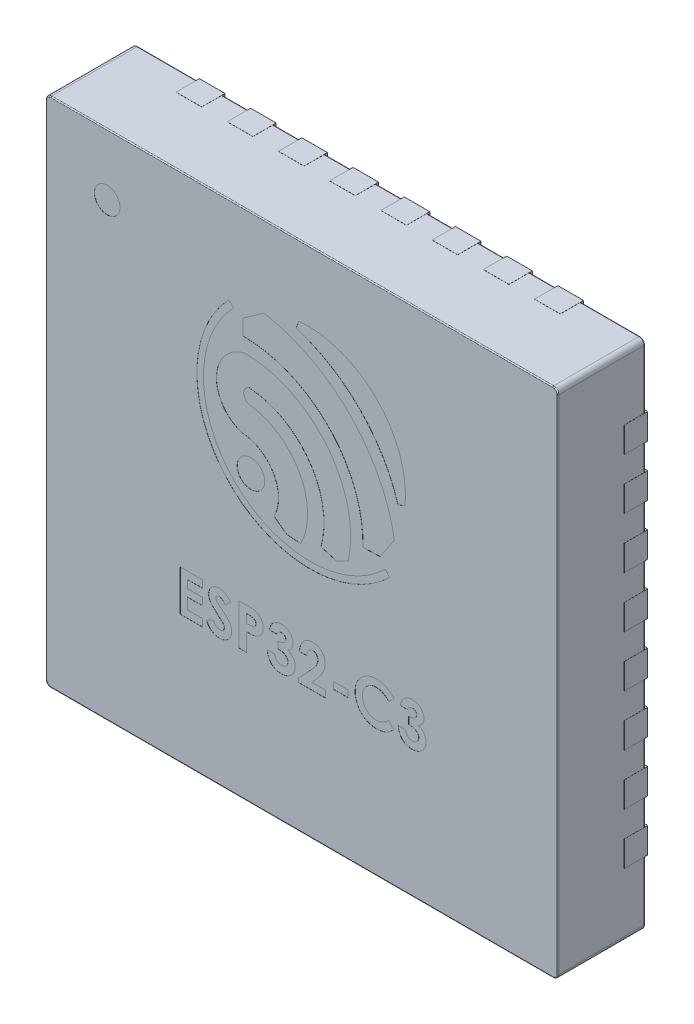
SolidWorks part; units mm, degrees
other "ESP32-C3-SoC" parameters "D5"=0.3678, "D12"=0.3401, "D13"=0.0424, "D1"=3.1308, "D2"=3.0402, "D3"=0.4115, "D4"=0.3, "D6"=0.3296, "D7"=0.2637, "D8"=0.9806, "D10"=0.5, "D11"=0.25, "D9"=4
ref_plane "Front Plane" through (0, 0, 0) normal (0, 0, 1) x (1, 0, 0)
ref_plane "Top Plane" through (0, 0, 0) normal (0, 1, 0) x (1, 0, 0)
ref_plane "Right Plane" through (0, 0, 0) normal (1, 0, 0) x (0, 0, -1)
sketch "Sketch1" plane through (0, 0, 0) normal (0, 1, 0) x (1, 0, 0)
  line L1 (-2.5, -2.5) -> (2.5, -2.5)
  line L2 (-2.5, -2.5) -> (-2.5, 2.5)
  line L3 (-2.5, 2.5) -> (2.5, 2.5)
  line L4 (2.5, -2.5) -> (2.5, 2.5)
  line L5 (-2.5, -2.5) -> (2.5, 2.5) construction
  line L6 (-2.5, 2.5) -> (2.5, -2.5) construction
  point P0 (0, 0)
  dimension "D1" = 5
  dimension "D2" = 5
extrude "Boss-Extrude1" add sketch "Sketch1" along normal blind 0.85
fillet "Fillet1" radius 0.05 4 edges at (2.5, 0.425, -2.5) (2.5, 0.425, 2.5) (-2.5, 0.425, 2.5) (-2.5, 0.425, -2.5)
fillet "Fillet2" radius 0.01 16 edges at (2.4854, 0.85, 2.4854) (0, 0.85, 2.5) (-2.4854, 0.85, 2.4854) (-2.5, 0.85, 0) (-2.4854, 0.85, -2.4854) (0, 0.85, -2.5) (2.4854, 0.85, -2.4854) (2.5, 0.85, 0) (2.5, 0, 0) (2.4854, 0, -2.4854) (0, 0, -2.5) (2.4854, 0, 2.4854) (0, 0, 2.5) (-2.4854, 0, 2.4854) (-2.5, 0, 0) (-2.4854, 0, -2.4854)
sketch "Sketch2" plane through (0, 0, 0) normal (0, -1, 0) x (1, 0, 0)
  line L0 (1.5573, 1.8427) -> (1.8427, 1.5573)
  line L1 (-1.825, -1.85) -> (1.825, -1.85)
  line L2 (-1.85, -1.825) -> (-1.85, 1.825)
  line L3 (-1.825, 1.85) -> (1.5396, 1.85)
  line L4 (1.85, -1.825) -> (1.85, 1.5396)
  line L5 (-1.8427, -1.8427) -> (1.85, 1.85) construction
  line L6 (-1.8427, 1.8427) -> (1.8427, -1.8427) construction
  line L7 (1.55, 1.85) -> (1.85, 1.85) construction
  line L8 (1.85, 1.55) -> (1.85, 1.85) construction
  line L9 (-1.85, 1.85) -> (-1.825, 1.85) construction
  line L10 (-1.85, 1.85) -> (-1.8427, 1.8427) construction
  line L11 (-1.85, 1.825) -> (-1.85, 1.85) construction
  line L12 (-1.85, -1.85) -> (-1.85, -1.825) construction
  line L13 (-1.85, -1.85) -> (-1.8427, -1.8427) construction
  line L14 (-1.85, -1.85) -> (-1.825, -1.85) construction
  line L15 (1.85, -1.85) -> (1.85, -1.825) construction
  line L16 (1.8427, -1.8427) -> (1.85, -1.85) construction
  line L17 (1.825, -1.85) -> (1.85, -1.85) construction
  line L18 (0, -1000) -> (0, 49000) construction
  line L23 (-0.375, 2.501) -> (-0.125, 2.501)
  line L24 (-0.375, 2.501) -> (-0.375, 2.101)
  line L25 (-0.375, 2.101) -> (-0.125, 2.101)
  line L26 (-0.125, 2.501) -> (-0.125, 2.101)
  line L27 (-0.375, 2.501) -> (-0.125, 2.101) construction
  line L28 (-0.375, 2.101) -> (-0.125, 2.501) construction
  line L30 (-0.875, 2.501) -> (-0.875, 2.101)
  line L31 (-0.875, 2.501) -> (-0.625, 2.501)
  line L32 (-0.625, 2.501) -> (-0.625, 2.101)
  line L33 (-0.875, 2.101) -> (-0.625, 2.101)
  line L34 (-0.875, 2.101) -> (-0.625, 2.501) construction
  line L35 (-0.875, 2.501) -> (-0.625, 2.101) construction
  line L36 (-1.375, 2.501) -> (-1.375, 2.101)
  line L37 (-1.375, 2.501) -> (-1.125, 2.501)
  line L38 (-1.125, 2.501) -> (-1.125, 2.101)
  line L39 (-1.375, 2.101) -> (-1.125, 2.101)
  line L40 (-1.375, 2.101) -> (-1.125, 2.501) construction
  line L41 (-1.375, 2.501) -> (-1.125, 2.101) construction
  line L42 (-1.875, 2.501) -> (-1.875, 2.101)
  line L43 (-1.875, 2.501) -> (-1.625, 2.501)
  line L44 (-1.625, 2.501) -> (-1.625, 2.101)
  line L45 (-1.875, 2.101) -> (-1.625, 2.101)
  line L46 (-1.875, 2.101) -> (-1.625, 2.501) construction
  line L47 (-1.875, 2.501) -> (-1.625, 2.101) construction
  line L48 (-0.375, 2.501) -> (-0.875, 2.501) construction
  line L49 (1.5396, 1.85) -> (1.55, 1.85) construction
  line L66 (1.55, 1.85) -> (1.5573, 1.8427) construction
  line L162 (-1000, 0) -> (49000, 0) construction
  line L163 (-2.5, 2.5) -> (2.5, 2.5) construction
  line L164 (0.375, 2.501) -> (0.875, 2.501) construction
  line L165 (1.875, 2.501) -> (1.625, 2.101) construction
  line L166 (1.875, 2.101) -> (1.625, 2.501) construction
  line L167 (1.375, 2.501) -> (1.125, 2.101) construction
  line L168 (1.375, 2.101) -> (1.125, 2.501) construction
  line L169 (0.875, 2.501) -> (0.625, 2.101) construction
  line L170 (0.875, 2.101) -> (0.625, 2.501) construction
  line L171 (0.375, 2.101) -> (0.125, 2.501) construction
  line L172 (0.375, 2.501) -> (0.125, 2.101) construction
  line L173 (1.875, 2.101) -> (1.625, 2.101)
  line L174 (1.625, 2.501) -> (1.625, 2.101)
  line L175 (1.875, 2.501) -> (1.625, 2.501)
  line L176 (1.875, 2.501) -> (1.875, 2.101)
  line L177 (1.375, 2.101) -> (1.125, 2.101)
  line L178 (1.125, 2.501) -> (1.125, 2.101)
  line L179 (1.375, 2.501) -> (1.125, 2.501)
  line L180 (1.375, 2.501) -> (1.375, 2.101)
  line L181 (0.875, 2.101) -> (0.625, 2.101)
  line L182 (0.625, 2.501) -> (0.625, 2.101)
  line L183 (0.875, 2.501) -> (0.625, 2.501)
  line L184 (0.875, 2.501) -> (0.875, 2.101)
  line L185 (0.125, 2.501) -> (0.125, 2.101)
  line L186 (0.375, 2.101) -> (0.125, 2.101)
  line L187 (0.375, 2.501) -> (0.375, 2.101)
  line L188 (0.375, 2.501) -> (0.125, 2.501)
  line L189 (0.375, -2.501) -> (0.125, -2.101) construction
  line L190 (0.375, -2.101) -> (0.125, -2.501) construction
  line L191 (0.875, -2.101) -> (0.625, -2.501) construction
  line L192 (0.875, -2.501) -> (0.625, -2.101) construction
  line L193 (1.375, -2.101) -> (1.125, -2.501) construction
  line L194 (1.375, -2.501) -> (1.125, -2.101) construction
  line L195 (1.875, -2.101) -> (1.625, -2.501) construction
  line L196 (1.875, -2.501) -> (1.625, -2.101) construction
  line L197 (0.375, -2.501) -> (0.875, -2.501) construction
  line L198 (-0.375, -2.501) -> (-0.875, -2.501) construction
  line L199 (-1.875, -2.501) -> (-1.625, -2.101) construction
  line L200 (-1.875, -2.101) -> (-1.625, -2.501) construction
  line L201 (-1.375, -2.501) -> (-1.125, -2.101) construction
  line L202 (-1.375, -2.101) -> (-1.125, -2.501) construction
  line L203 (-0.875, -2.501) -> (-0.625, -2.101) construction
  line L204 (-0.875, -2.101) -> (-0.625, -2.501) construction
  line L205 (-0.375, -2.101) -> (-0.125, -2.501) construction
  line L206 (-0.375, -2.501) -> (-0.125, -2.101) construction
  line L207 (0.375, -2.501) -> (0.125, -2.501)
  line L208 (0.375, -2.501) -> (0.375, -2.101)
  line L209 (0.375, -2.101) -> (0.125, -2.101)
  line L210 (0.125, -2.501) -> (0.125, -2.101)
  line L211 (0.875, -2.501) -> (0.875, -2.101)
  line L212 (0.875, -2.501) -> (0.625, -2.501)
  line L213 (0.625, -2.501) -> (0.625, -2.101)
  line L214 (0.875, -2.101) -> (0.625, -2.101)
  line L215 (1.375, -2.501) -> (1.375, -2.101)
  line L216 (1.375, -2.501) -> (1.125, -2.501)
  line L217 (1.125, -2.501) -> (1.125, -2.101)
  line L218 (1.375, -2.101) -> (1.125, -2.101)
  line L219 (1.875, -2.501) -> (1.875, -2.101)
  line L220 (1.875, -2.501) -> (1.625, -2.501)
  line L221 (1.625, -2.501) -> (1.625, -2.101)
  line L222 (1.875, -2.101) -> (1.625, -2.101)
  line L223 (-1.875, -2.101) -> (-1.625, -2.101)
  line L224 (-1.625, -2.501) -> (-1.625, -2.101)
  line L225 (-1.875, -2.501) -> (-1.625, -2.501)
  line L226 (-1.875, -2.501) -> (-1.875, -2.101)
  line L227 (-1.375, -2.101) -> (-1.125, -2.101)
  line L228 (-1.125, -2.501) -> (-1.125, -2.101)
  line L229 (-1.375, -2.501) -> (-1.125, -2.501)
  line L230 (-1.375, -2.501) -> (-1.375, -2.101)
  line L231 (-0.875, -2.101) -> (-0.625, -2.101)
  line L232 (-0.625, -2.501) -> (-0.625, -2.101)
  line L233 (-0.875, -2.501) -> (-0.625, -2.501)
  line L234 (-0.875, -2.501) -> (-0.875, -2.101)
  line L235 (-0.125, -2.501) -> (-0.125, -2.101)
  line L236 (-0.375, -2.101) -> (-0.125, -2.101)
  line L237 (-0.375, -2.501) -> (-0.375, -2.101)
  line L238 (-0.375, -2.501) -> (-0.125, -2.501)
  line L239 (2.501, 0.375) -> (2.101, 0.125) construction
  line L240 (2.101, 0.375) -> (2.501, 0.125) construction
  line L241 (2.101, 0.875) -> (2.501, 0.625) construction
  line L242 (2.501, 0.875) -> (2.101, 0.625) construction
  line L243 (2.101, 1.375) -> (2.501, 1.125) construction
  line L244 (2.501, 1.375) -> (2.101, 1.125) construction
  line L245 (2.101, 1.875) -> (2.501, 1.625) construction
  line L246 (2.501, 1.875) -> (2.101, 1.625) construction
  line L247 (2.501, 0.375) -> (2.501, 0.875) construction
  line L248 (2.501, -0.375) -> (2.501, -0.875) construction
  line L249 (2.501, -1.875) -> (2.101, -1.625) construction
  line L250 (2.101, -1.875) -> (2.501, -1.625) construction
  line L251 (2.501, -1.375) -> (2.101, -1.125) construction
  line L252 (2.101, -1.375) -> (2.501, -1.125) construction
  line L253 (2.501, -0.875) -> (2.101, -0.625) construction
  line L254 (2.101, -0.875) -> (2.501, -0.625) construction
  line L255 (2.101, -0.375) -> (2.501, -0.125) construction
  line L256 (2.501, -0.375) -> (2.101, -0.125) construction
  line L257 (2.501, 0.375) -> (2.501, 0.125)
  line L258 (2.501, 0.375) -> (2.101, 0.375)
  line L259 (2.101, 0.375) -> (2.101, 0.125)
  line L260 (2.501, 0.125) -> (2.101, 0.125)
  line L261 (2.501, 0.875) -> (2.101, 0.875)
  line L262 (2.501, 0.875) -> (2.501, 0.625)
  line L263 (2.501, 0.625) -> (2.101, 0.625)
  line L264 (2.101, 0.875) -> (2.101, 0.625)
  line L265 (2.501, 1.375) -> (2.101, 1.375)
  line L266 (2.501, 1.375) -> (2.501, 1.125)
  line L267 (2.501, 1.125) -> (2.101, 1.125)
  line L268 (2.101, 1.375) -> (2.101, 1.125)
  line L269 (2.501, 1.875) -> (2.101, 1.875)
  line L270 (2.501, 1.875) -> (2.501, 1.625)
  line L271 (2.501, 1.625) -> (2.101, 1.625)
  line L272 (2.101, 1.875) -> (2.101, 1.625)
  line L273 (2.101, -1.875) -> (2.101, -1.625)
  line L274 (2.501, -1.625) -> (2.101, -1.625)
  line L275 (2.501, -1.875) -> (2.501, -1.625)
  line L276 (2.501, -1.875) -> (2.101, -1.875)
  line L277 (2.101, -1.375) -> (2.101, -1.125)
  line L278 (2.501, -1.125) -> (2.101, -1.125)
  line L279 (2.501, -1.375) -> (2.501, -1.125)
  line L280 (2.501, -1.375) -> (2.101, -1.375)
  line L281 (2.101, -0.875) -> (2.101, -0.625)
  line L282 (2.501, -0.625) -> (2.101, -0.625)
  line L283 (2.501, -0.875) -> (2.501, -0.625)
  line L284 (2.501, -0.875) -> (2.101, -0.875)
  line L285 (2.501, -0.125) -> (2.101, -0.125)
  line L286 (2.101, -0.375) -> (2.101, -0.125)
  line L287 (2.501, -0.375) -> (2.101, -0.375)
  line L288 (2.501, -0.375) -> (2.501, -0.125)
  line L289 (-2.501, -0.375) -> (-2.101, -0.125) construction
  line L290 (-2.101, -0.375) -> (-2.501, -0.125) construction
  line L291 (-2.101, -0.875) -> (-2.501, -0.625) construction
  line L292 (-2.501, -0.875) -> (-2.101, -0.625) construction
  line L293 (-2.101, -1.375) -> (-2.501, -1.125) construction
  line L294 (-2.501, -1.375) -> (-2.101, -1.125) construction
  line L295 (-2.101, -1.875) -> (-2.501, -1.625) construction
  line L296 (-2.501, -1.875) -> (-2.101, -1.625) construction
  line L297 (-2.501, -0.375) -> (-2.501, -0.875) construction
  line L298 (-2.501, 0.375) -> (-2.501, 0.875) construction
  line L299 (-2.501, 1.875) -> (-2.101, 1.625) construction
  line L300 (-2.101, 1.875) -> (-2.501, 1.625) construction
  line L301 (-2.501, 1.375) -> (-2.101, 1.125) construction
  line L302 (-2.101, 1.375) -> (-2.501, 1.125) construction
  line L303 (-2.501, 0.875) -> (-2.101, 0.625) construction
  line L304 (-2.101, 0.875) -> (-2.501, 0.625) construction
  line L305 (-2.101, 0.375) -> (-2.501, 0.125) construction
  line L306 (-2.501, 0.375) -> (-2.101, 0.125) construction
  line L307 (-2.501, -0.375) -> (-2.501, -0.125)
  line L308 (-2.501, -0.375) -> (-2.101, -0.375)
  line L309 (-2.101, -0.375) -> (-2.101, -0.125)
  line L310 (-2.501, -0.125) -> (-2.101, -0.125)
  line L311 (-2.501, -0.875) -> (-2.101, -0.875)
  line L312 (-2.501, -0.875) -> (-2.501, -0.625)
  line L313 (-2.501, -0.625) -> (-2.101, -0.625)
  line L314 (-2.101, -0.875) -> (-2.101, -0.625)
  line L315 (-2.501, -1.375) -> (-2.101, -1.375)
  line L316 (-2.501, -1.375) -> (-2.501, -1.125)
  line L317 (-2.501, -1.125) -> (-2.101, -1.125)
  line L318 (-2.101, -1.375) -> (-2.101, -1.125)
  line L319 (-2.501, -1.875) -> (-2.101, -1.875)
  line L320 (-2.501, -1.875) -> (-2.501, -1.625)
  line L321 (-2.501, -1.625) -> (-2.101, -1.625)
  line L322 (-2.101, -1.875) -> (-2.101, -1.625)
  line L323 (-2.101, 1.875) -> (-2.101, 1.625)
  line L324 (-2.501, 1.625) -> (-2.101, 1.625)
  line L325 (-2.501, 1.875) -> (-2.501, 1.625)
  line L326 (-2.501, 1.875) -> (-2.101, 1.875)
  line L327 (-2.101, 1.375) -> (-2.101, 1.125)
  line L328 (-2.501, 1.125) -> (-2.101, 1.125)
  line L329 (-2.501, 1.375) -> (-2.501, 1.125)
  line L330 (-2.501, 1.375) -> (-2.101, 1.375)
  line L331 (-2.101, 0.875) -> (-2.101, 0.625)
  line L332 (-2.501, 0.625) -> (-2.101, 0.625)
  line L333 (-2.501, 0.875) -> (-2.501, 0.625)
  line L334 (-2.501, 0.875) -> (-2.101, 0.875)
  line L335 (-2.501, 0.125) -> (-2.101, 0.125)
  line L336 (-2.101, 0.375) -> (-2.101, 0.125)
  line L337 (-2.501, 0.375) -> (-2.101, 0.375)
  line L338 (-2.501, 0.375) -> (-2.501, 0.125)
  line L339 (1.8427, 1.5573) -> (1.85, 1.55) construction
  line L340 (1.85, 1.5396) -> (1.85, 1.55) construction
  arc A0 (-1.825, 1.85) -> (-1.85, 1.825) centre (-1.825, 1.825) ccw
  arc A1 (-1.85, -1.825) -> (-1.825, -1.85) centre (-1.825, -1.825) ccw
  arc A2 (1.825, -1.85) -> (1.85, -1.825) centre (1.825, -1.825) ccw
  arc A3 (1.5573, 1.8427) -> (1.5396, 1.85) centre (1.5396, 1.825) ccw
  arc A5 (1.85, 1.5396) -> (1.8427, 1.5573) centre (1.825, 1.5396) ccw
  point P0 (0, 0)
  point P12 (-0.25, 2.301)
  point P60 (0.25, 2.301)
  point P93 (0.25, -2.301)
  point P94 (-0.25, -2.301)
  point P127 (2.301, 0.25)
  point P128 (2.301, -0.25)
  point P161 (-2.301, -0.25)
  point P162 (-2.301, 0.25)
  dimension "D5" = 0.05
  dimension "D12" = 0.05
  dimension "D13" = 0.05
  dimension "D1" = 3.7
  dimension "D2" = 3.7
  dimension "D4" = 45
  dimension "D6" = 0.4
  dimension "D7" = 0.25
  dimension "D8" = 0.25
  dimension "D11" = 0.001
  dimension "D3" = 0.3
extrude "Boss-Extrude2" add sketch "Sketch2" along normal blind 0.025 and the other way blind 0.203
sketch "Sketch3" plane through (0, 0.85, 0) normal (0, 1, 0) x (1, 0, 0)
  line L7 (-2.5, 1.245) -> (2.5, 1.245) construction
  line L8 (-2.5, 2.5) -> (-2.5, -2.5) construction
  line L10 (0, 2.49) -> (0, 0) construction
  line L11 (2.5, 2.45) -> (2.5, -2.45) construction
  line L12 (2.45, -2.5) -> (-2.45, -2.5) construction
  line L27 (-1000, 0) -> (49000, 0) construction
  line L28 (2.45, 2.49) -> (-2.45, 2.49) construction
  line L29 (-0.9389, -0.7409) -> (-1.0079, -0.7703)
  line L30 (0.0287, -1.8122) -> (0.055, -1.7389)
  line L31 (-0.596, -0.211) -> (-0.7661, -0.2183)
  line L32 (-0.7661, -0.2183) -> (-0.9036, -0.4282)
  line L33 (0.3683, -1.7097) -> (0.5747, -1.5649)
  line L34 (0.5747, -1.5649) -> (0.5747, -1.4127)
  line L35 (0.6651, -1.6054) -> (0.7132, -1.6479)
  line L36 (-0.8568, -0.0878) -> (-0.814, -0.1357)
  line L37 (0.2706, -0.0409) -> (0.1522, 0.0487)
  line L38 (0.1522, 0.0487) -> (0.0101, 0.0612)
  line L39 (-0.1861, -0.0114) -> (-0.3363, 0.0334)
  line L40 (-0.3363, 0.0334) -> (-0.4534, -0.0252)
  circle A12 centre (1.9, -1.9) radius 0.125
  arc A48 (-0.9389, -0.7409) -> (0.055, -1.7389) centre (0.4965, -0.3053) ccw
  arc A49 (-0.9036, -0.4282) -> (0.3683, -1.7097) centre (0.6484, -0.1598) ccw
  arc A50 (0.5574, -1.277) -> (0.5869, -0.59) centre (0.477, -0.9294) ccw
  arc A51 (0.7132, -1.6479) -> (-0.8568, -0.0878) centre (-0.0819, -0.878) ccw
  circle A52 centre (0.4965, -0.2888) radius 0.1343
  arc A53 (-0.1861, -0.0114) -> (0.5144, -1.0054) centre (0.5639, -0.2267) ccw
  arc A54 (0.2706, -0.0409) -> (0.5869, -0.59) centre (0.603, -0.2151) ccw
  arc A55 (0.0101, 0.0612) -> (0.517, -0.8644) centre (0.5886, -0.2236) ccw
  arc A56 (-0.4534, -0.0252) -> (0.5574, -1.277) centre (0.5578, -0.2427) ccw
  arc A57 (0.6651, -1.6054) -> (-0.814, -0.1357) centre (-0.0819, -0.878) ccw
  arc A58 (-0.596, -0.211) -> (0.5747, -1.4127) centre (0.5735, -0.2428) ccw
  arc A59 (0.517, -0.8644) -> (0.5144, -1.0054) centre (0.4933, -0.9345) cw
  arc A60 (-1.0079, -0.7703) -> (0.0287, -1.8122) centre (-0.0509, -0.8547) ccw
  text T0 "ESP32-C3" font "Century Gothic" height 0.4
  point P0 (0, 0)
  point P7 (0, 1.245)
  point P21 (0, 0)
  dimension "D2" = 0.25
  dimension "D3" = 0.6
  dimension "D4" = 0.6
extrude "Cut-Extrude1" cut sketch "Sketch3" against normal blind 0.001
move or copy body "Body-Move/Copy1" bodies to move or copy 131 copy no rotation origin (0, 0, 0) rotation axis (0, 0.7071, 0.7071) rotation angle 180
move or copy body "Body-Move/Copy2" bodies to move or copy 132 copy no translate (0, 0, 0.025)
equation "\"D8@Sketch2\"=\"D10@Sketch2\"/2"
equation "\"D1@Sketch1\"=\"D2@Sketch1\""
equation "\"D4@Sketch3\"=\"D3@Sketch3\""
equation "\"D1@Sketch2\"=\"D2@Sketch2\""
equation "\"D12@Sketch2\"=\"D5@Sketch2\""
equation "\"D13@Sketch2\"=\"D5@Sketch2\""
